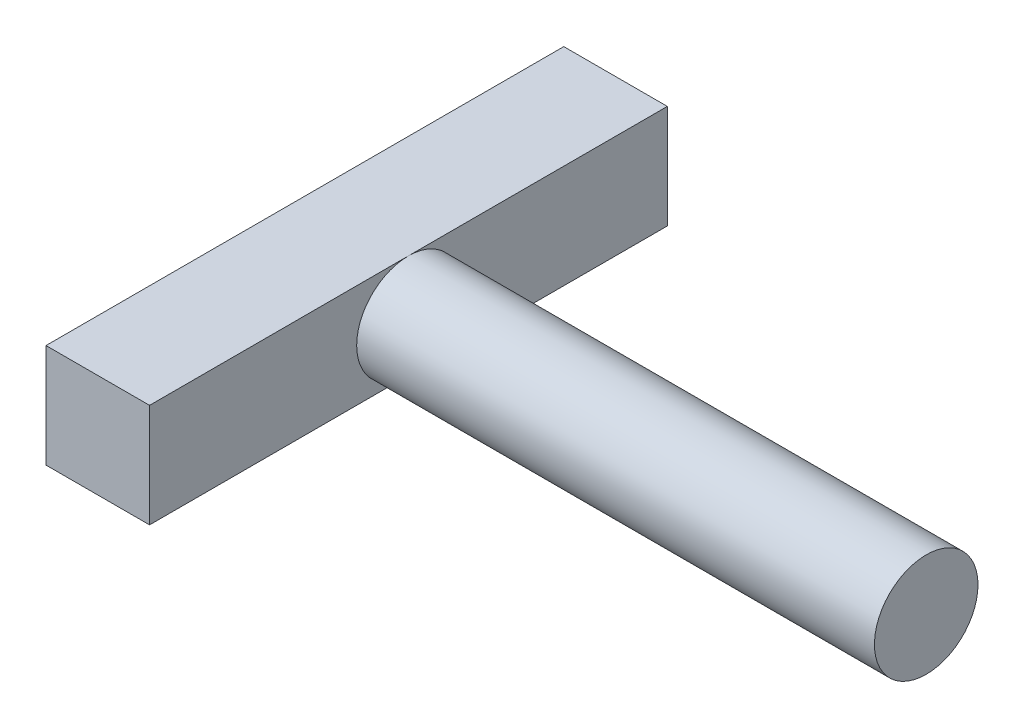
SolidWorks part; units mm, degrees
ref_plane "Front Plane" through (0, 0, 0) normal (0, 0, 1) x (1, 0, 0)
ref_plane "Top Plane" through (0, 0, 0) normal (0, 1, 0) x (1, 0, 0)
ref_plane "Right Plane" through (0, 0, 0) normal (1, 0, 0) x (0, 0, -1)
sketch "Sketch1" plane through (0, 0, 0) normal (0, 0, 1) x (1, 0, 0)
  line L1 (-12.7, 12.7) -> (12.7, 12.7)
  line L2 (-12.7, 12.7) -> (-12.7, -12.7)
  line L3 (-12.7, -12.7) -> (12.7, -12.7)
  line L4 (12.7, 12.7) -> (12.7, -12.7)
  line L5 (-12.7, 12.7) -> (12.7, -12.7) construction
  line L6 (-12.7, -12.7) -> (12.7, 12.7) construction
  point P0 (0, 0)
  point P11 (0, 0)
  dimension "D1" = 25.4
  dimension "D3" = 25.4
extrude "Boss-Extrude1" add sketch "Sketch1" along normal blind 127
sketch "Sketch2" plane through (12.7, 0, 0) normal (1, 0, 0) x (0, 0, -1)
  line L0 (-63.5, 12.7) -> (-63.5, -12.7) construction
  line L1 (-127, 12.7) -> (0, 12.7) construction
  line L2 (-127, -12.7) -> (0, -12.7) construction
  circle A0 centre (-63.5, 0) radius 12.7
extrude "Boss-Extrude2" add sketch "Sketch2" along normal blind 127
